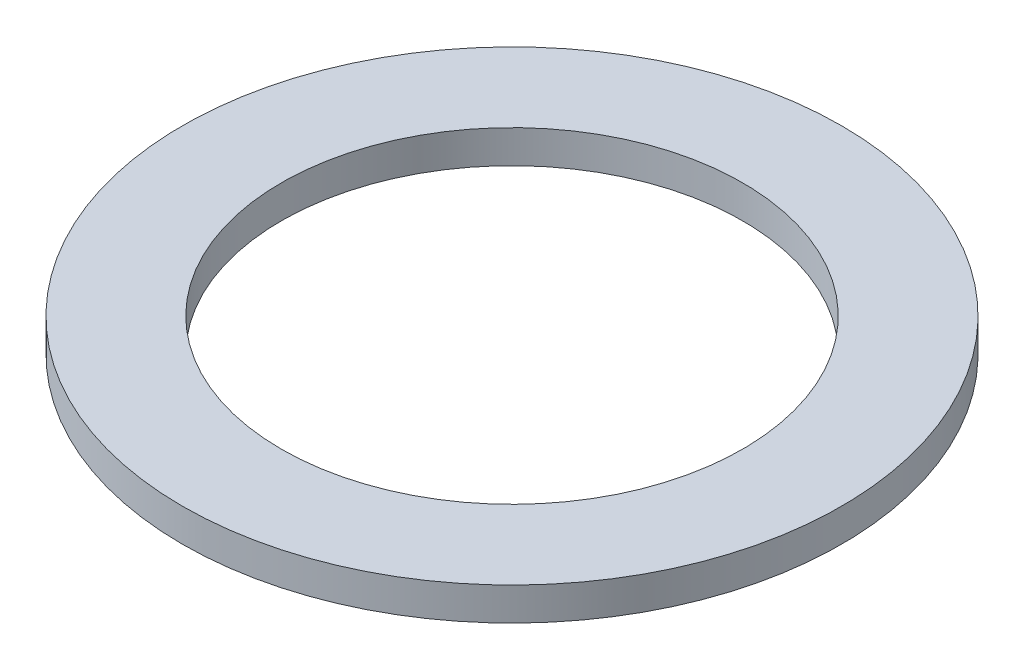
SolidWorks part; units mm, degrees
ref_plane "前视基准面" through (0, 0, 0) normal (0, 0, 1) x (1, 0, 0)
ref_plane "上视基准面" through (0, 0, 0) normal (0, 1, 0) x (1, 0, 0)
ref_plane "右视基准面" through (0, 0, 0) normal (1, 0, 0) x (0, 0, -1)
sketch "草图1" plane through (0, 0, 0) normal (0, 1, 0) x (1, 0, 0)
  circle A0 centre (0, 0) radius 7
  circle A1 centre (0, 0) radius 10
  dimension "D1" = 14
  dimension "D2" = 20
extrude "凸台-拉伸1" add sketch "草图1" along normal blind 1
